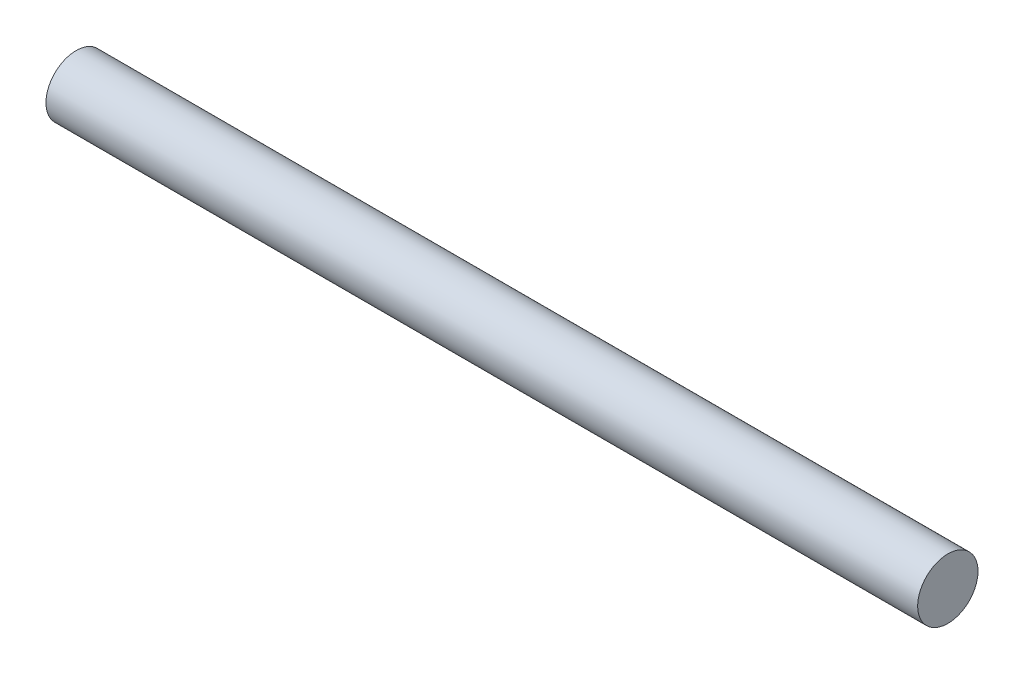
SolidWorks part; units mm, degrees
material "Hexcel AS4C (3000 Filaments)"
ref_plane "Front Plane" through (0, 0, 0) normal (0, 0, 1) x (1, 0, 0)
ref_plane "Top Plane" through (0, 0, 0) normal (0, 1, 0) x (1, 0, 0)
ref_plane "Right Plane" through (0, 0, 0) normal (1, 0, 0) x (0, 0, -1)
sketch "Sketch1" plane through (0, 0, 0) normal (1, 0, 0) x (0, 0, -1)
  circle A0 centre (0, 0) radius 25.4
  dimension "D1" = 50.8
extrude "Boss-Extrude1" add sketch "Sketch1" along normal blind 734.314
scale "Scale1" scale about centroid uniform scaling yes scale factor 0.5867
